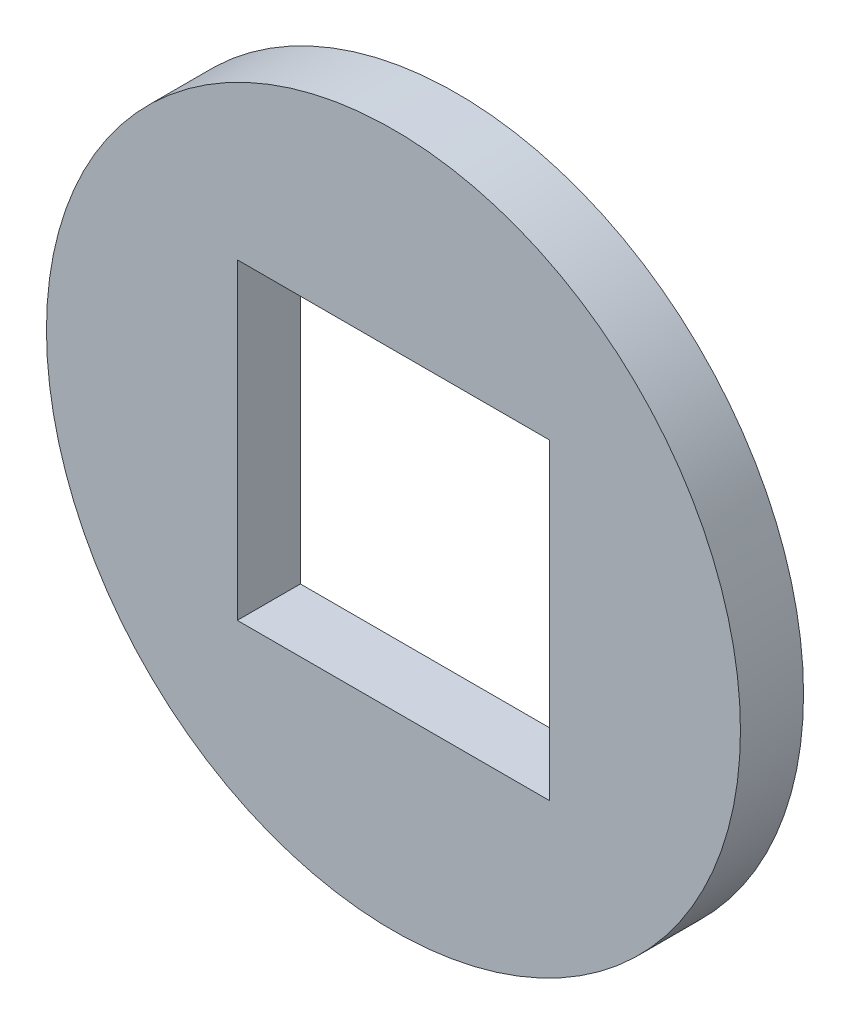
SolidWorks part; units mm, degrees
ref_plane "Plan de face" through (0, 0, 0) normal (0, 0, 1) x (1, 0, 0)
ref_plane "Plan de dessus" through (0, 0, 0) normal (0, 1, 0) x (1, 0, 0)
ref_plane "Plan de droite" through (0, 0, 0) normal (1, 0, 0) x (0, 0, -1)
sketch "Esquisse1" plane through (0, 0, 0) normal (0, 0, 1) x (1, 0, 0)
  line L0 (-2.4749, 2.4749) -> (2.4749, -2.4749) construction
  line L1 (-2.4749, 2.4749) -> (2.4749, 2.4749)
  line L2 (-2.4749, 2.4749) -> (-2.4749, -2.4749)
  line L3 (-2.4749, -2.4749) -> (2.4749, -2.4749)
  line L4 (2.4749, 2.4749) -> (2.4749, -2.4749)
  circle A0 centre (0, 0) radius 5.5
  dimension "D1" = 11
  dimension "D2" = 7
extrude "Extrusion1" add sketch "Esquisse1" along normal blind 1
